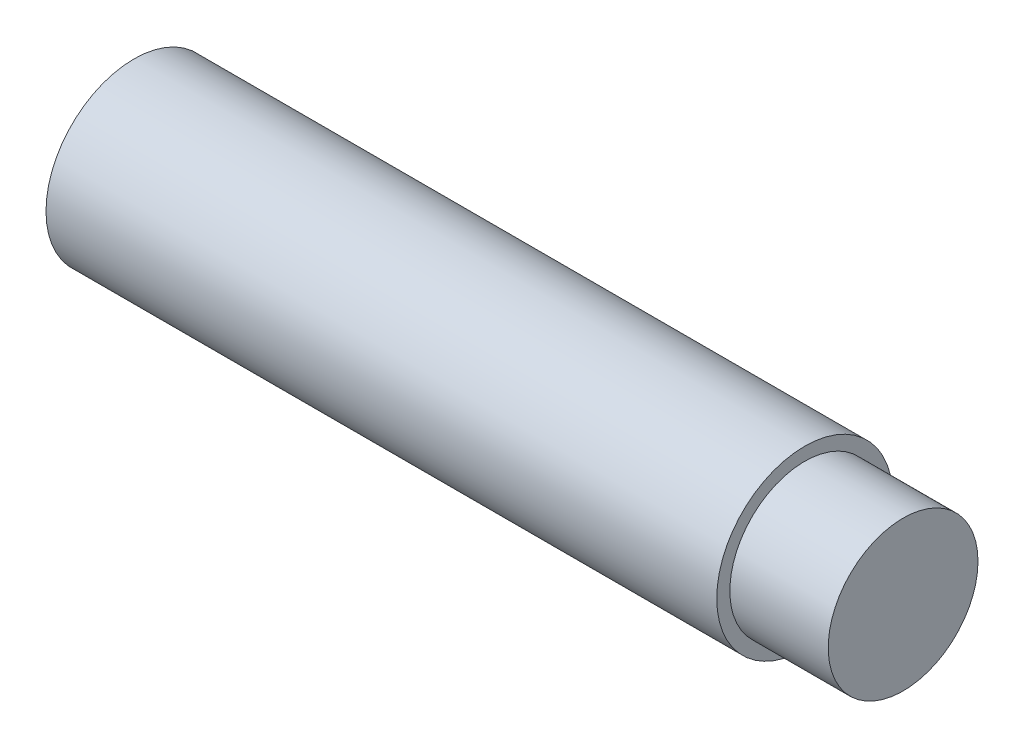
SolidWorks part; units mm, degrees
material "Cast Alloy Steel"
ref_plane "Front Plane" through (0, 0, 0) normal (0, 0, 1) x (1, 0, 0)
ref_plane "Top Plane" through (0, 0, 0) normal (0, 1, 0) x (1, 0, 0)
ref_plane "Right Plane" through (0, 0, 0) normal (1, 0, 0) x (0, 0, -1)
sketch "Sketch1" plane through (0, 0, 0) normal (1, 0, 0) x (0, 0, -1)
  circle A0 centre (0, 0) radius 3.935
  dimension "D1" = 7.87
extrude "Boss-Extrude1" add sketch "Sketch1" along normal blind 30
sketch "Sketch2" plane through (30, 0, 0) normal (1, 0, 0) x (0, 0, -1)
  circle A0 centre (0, 0) radius 3.35
  dimension "D1" = 6.7
extrude "Boss-Extrude2" add sketch "Sketch2" along normal blind 4.4
